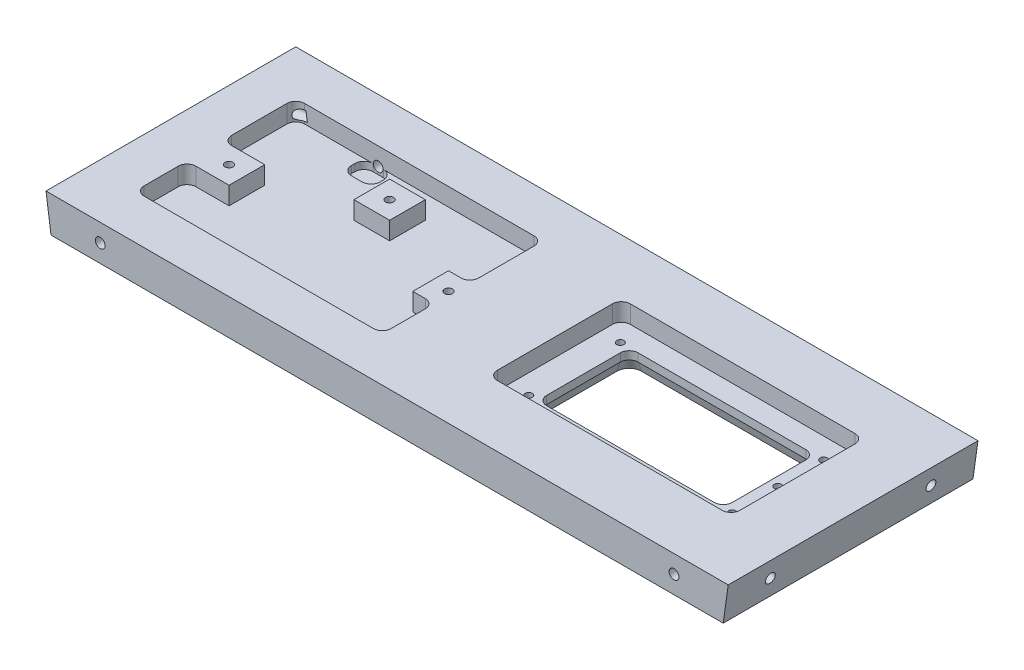
SolidWorks part; units mm, degrees
material "Oak"
ref_plane "Front Plane" through (0, 0, 0) normal (0, 0, 1) x (1, 0, 0)
ref_plane "Top Plane" through (0, 0, 0) normal (0, 1, 0) x (1, 0, 0)
ref_plane "Right Plane" through (0, 0, 0) normal (1, 0, 0) x (0, 0, -1)
sketch "Sketch1" plane through (0, 0, 0) normal (0, 0, 1) x (1, 0, 0)
  line L0 (0, 0) -> (0, -87.7011) construction
  line L1 (188.4017, -20) -> (-188.4017, -20)
  line L2 (-188.4017, -20) -> (-191.2125, 0)
  line L3 (-198.4942, -20.0415) -> (-240.8028, 281) construction
  line L4 (-191.2125, 0) -> (191.2125, 0)
  line L6 (188.4017, -20) -> (191.2125, 0)
  point P12 (0, 0)
  point P13 (0, -20)
  dimension "D1" = 20
  dimension "D2" = 10
extrude "Boss-Extrude1" add sketch "Sketch1" along normal blind 140
sketch "Sketch2" plane through (0, 0, 0) normal (0, 1, 0) x (1, 0, 0)
  line L0 (153.3, -105.5) -> (27.3, -105.5)
  line L1 (153.3, -100.5) -> (27.3, -100.5) construction
  line L2 (153.3, -100.5) -> (153.3, -36) construction
  line L3 (153.3, -36) -> (27.3, -36) construction
  line L4 (27.3, -100.5) -> (27.3, -36) construction
  line L5 (22.3, -100.5) -> (22.3, -36)
  line L6 (153.3, -31) -> (27.3, -31)
  line L7 (158.3, -100.5) -> (158.3, -36)
  line L8 (158.3, -31) -> (22.3, -31) construction
  line L9 (158.3, -105.5) -> (158.3, -31) construction
  line L10 (22.3, -105.5) -> (22.3, -31) construction
  line L11 (158.3, -105.5) -> (22.3, -105.5) construction
  arc A0 (153.3, -31) -> (158.3, -36) centre (153.3, -36) cw
  arc A1 (22.3, -36) -> (27.3, -31) centre (27.3, -36) cw
  arc A2 (27.3, -105.5) -> (22.3, -100.5) centre (27.3, -100.5) cw
  arc A3 (153.3, -105.5) -> (158.3, -100.5) centre (153.3, -100.5) ccw
  dimension "D2" = 5
  dimension "D1" = 5
extrude "Cut-Extrude1" cut sketch "Sketch2" against normal blind 10
sketch "Sketch3" plane through (0, -10, 0) normal (0, 1, 0) x (1, 0, 0)
  circle A0 centre (147.3, -42.6) radius 2
  circle A1 centre (147.3, -68.25) radius 2
  circle A2 centre (147.3, -93.9) radius 2
  circle A3 centre (33.3, -93.9) radius 2
  circle A4 centre (33.3, -42.6) radius 2
  dimension "D1" = 4
extrude "Cut-Extrude2" cut sketch "Sketch3" against normal blind 10
sketch "Sketch4" plane through (0, -10, 0) normal (0, 1, 0) x (1, 0, 0)
  line L1 (137.3, -93.9) -> (43.3, -93.9)
  line L2 (142.3, -88.9) -> (142.3, -47.6)
  line L3 (137.3, -42.6) -> (43.3, -42.6)
  line L4 (38.3, -88.9) -> (38.3, -47.6)
  arc A0 (142.3, -47.6) -> (137.3, -42.6) centre (137.3, -47.6) ccw
  arc A1 (43.3, -42.6) -> (38.3, -47.6) centre (43.3, -47.6) ccw
  arc A2 (43.3, -93.9) -> (38.3, -88.9) centre (43.3, -88.9) cw
  arc A3 (137.3, -93.9) -> (142.3, -88.9) centre (137.3, -88.9) ccw
  circle A4 centre (147.3, -68.25) radius 2 construction
  circle A5 centre (33.3, -42.6) radius 2 construction
  circle A6 centre (147.3, -42.6) radius 2 construction
  circle A7 centre (147.3, -93.9) radius 2 construction
  point P10 (38.3, -42.6)
  point P15 (142.3, -93.9)
  dimension "D1" = 5
  dimension "D2" = 5
  dimension "D3" = 5
  dimension "D4" = 0
  dimension "D5" = 0
extrude "Cut-Extrude3" cut sketch "Sketch4" against normal through all
chamfer "Chamfer2" distance 2 angle 70 8 edges at (90.3, -20, 93.9) (140.8355, -20, 92.4355) (39.7645, -20, 92.4355) (142.3, -20, 68.25) (38.3, -20, 68.25) (140.8355, -20, 44.0645) (39.7645, -20, 44.0645) (90.3, -20, 42.6)
sketch "Sketch5" plane through (0, -20, 0) normal (0, -1, 0) x (1, 0, 0)
  circle A0 centre (147.3, 42.6) radius 3.5
  circle A1 centre (147.3, 68.25) radius 3.5
  circle A2 centre (147.3, 93.9) radius 3.5
  circle A3 centre (33.3, 93.9) radius 3.5
  circle A4 centre (33.3, 42.6) radius 3.5
  dimension "D1" = 7
extrude "Cut-Extrude4" cut sketch "Sketch5" against normal blind 4
sketch "Sketch6" plane through (0, 0, 0) normal (0, 1, 0) x (1, 0, 0)
  circle A0 centre (-29.7, -75.9) radius 2.25
  circle A1 centre (-90.7, -47.9) radius 2.25
  circle A2 centre (-152.7, -75.9) radius 2.25
  dimension "D1" = 4.5
extrude "Cut-Extrude5" cut sketch "Sketch6" against normal through all
sketch "Sketch7" plane through (0, -20, 0) normal (0, -1, 0) x (1, 0, 0)
  circle A0 centre (-29.7, 75.9) radius 3.5
  circle A1 centre (-90.7, 47.9) radius 3.5
  circle A2 centre (-152.7, 75.9) radius 3.5
  dimension "D1" = 7
extrude "Cut-Extrude6" cut sketch "Sketch7" against normal blind 10
sketch "Sketch8" plane through (0, 0, 0) normal (0, 1, 0) x (1, 0, 0)
  line L0 (191.2125, 0) -> (-191.2125, 0) construction
  line L1 (191.2125, -12) -> (-191.2125, -12)
  line L2 (191.2125, -12) -> (191.2125, 0)
  line L3 (191.2125, 0) -> (-191.2125, 0)
  line L4 (-191.2125, -12) -> (-191.2125, 0)
  dimension "D1" = 12
extrude "Cut-Extrude7" [suppressed] cut sketch "Sketch8" against normal blind 1.5
sketch "Sketch9" plane through (-187.5089, -26.3527, 0) normal (-0.9903, -0.1392, 0) x (0, 0, 1)
  line L0 (70, -46.0258) -> (70, 104.6021) construction
  line L1 (140, -46.0258) -> (0, -46.0258) construction
  line L2 (140, 6.4151) -> (0, 6.4151) construction
  circle A0 centre (25, 16.5151) radius 2.75
  circle A1 centre (115, 16.5151) radius 2.75
  dimension "D1" = 90
  dimension "D3" = 5.5
  dimension "D2" = 10.1
extrude "Cut-Extrude8" cut sketch "Sketch9" against normal blind 30
mirror "Mirror1" about plane through (0, 0, 0) normal (1, 0, 0) of "Cut-Extrude8"
sketch "Sketch11" plane through (0, 0, 140) normal (0, 0, 1) x (1, 0, 0)
  line L1 (0, 98.6004) -> (0, -95.3458) construction
  line L2 (-188.4017, -20) -> (188.4017, -20) construction
  circle A0 centre (-160.8028, -10) radius 2.75
  circle A1 centre (160.8028, -10) radius 2.75
  dimension "D2" = 10
  dimension "D3" = 5.5
  dimension "D1" = 321.6056
extrude "Cut-Extrude9" cut sketch "Sketch11" against normal blind 30
sketch "Sketch12" plane through (0, 0, 0) normal (0, 0, -1) x (-1, 0, 0)
  line L0 (0, 0) -> (0, -85.5207) construction
  line L1 (188.4017, -20) -> (-188.4017, -20) construction
  circle A0 centre (120, -10) radius 2.75
  circle A1 centre (-120, -10) radius 2.75
  dimension "D1" = 5.5
  dimension "D3" = 10
  dimension "D2" = 120
  dimension "D4" = 240
extrude "Cut-Extrude10" cut sketch "Sketch12" against normal blind 30
sketch "Sketch13" plane through (0, 0, 0) normal (0, 1, 0) x (1, 0, 0)
  line L0 (-32.7, -115) -> (-161.2125, -115)
  line L1 (-166.2125, -110) -> (-166.2125, -90.9)
  line L2 (-161.2125, -85.9) -> (-142.7, -85.9)
  line L3 (-142.7, -85.9) -> (-142.7, -65.9)
  line L5 (-39.7, -65.9) -> (-39.7, -85.9)
  line L6 (-39.7, -85.9) -> (-32.7, -85.9)
  line L7 (-27.7, -90.9) -> (-27.7, -110)
  line L8 (-39.7, -65.9) -> (-32.7, -65.9)
  line L9 (-27.7, -60.9) -> (-27.7, -30)
  line L10 (-32.7, -25) -> (-161.2125, -25)
  line L11 (-166.2125, -30) -> (-166.2125, -60.9)
  line L12 (-161.2125, -65.9) -> (-142.7, -65.9)
  line L13 (-191.2125, -140) -> (-191.2125, 0) construction
  line L14 (-17.7, -123.8) -> (-17.7, -7.9) construction
  line L15 (191.2125, -140) -> (-191.2125, -140) construction
  line L16 (191.2125, 0) -> (-191.2125, 0) construction
  line L18 (-80.7, -57.9) -> (-100.7, -57.9)
  line L19 (-80.7, -57.9) -> (-80.7, -37.9)
  line L20 (-80.7, -37.9) -> (-100.7, -37.9)
  line L21 (-100.7, -57.9) -> (-100.7, -37.9)
  line L22 (-80.7, -57.9) -> (-100.7, -37.9) construction
  line L23 (-80.7, -37.9) -> (-100.7, -57.9) construction
  circle A0 centre (-152.7, -75.9) radius 2.25 construction
  circle A1 centre (-29.7, -75.9) radius 2 construction
  arc A2 (-32.7, -65.9) -> (-27.7, -60.9) centre (-32.7, -60.9) ccw
  arc A3 (-27.7, -30) -> (-32.7, -25) centre (-32.7, -30) ccw
  arc A4 (-161.2125, -25) -> (-166.2125, -30) centre (-161.2125, -30) ccw
  arc A5 (-166.2125, -60.9) -> (-161.2125, -65.9) centre (-161.2125, -60.9) ccw
  arc A6 (-166.2125, -90.9) -> (-161.2125, -85.9) centre (-161.2125, -90.9) cw
  arc A7 (-161.2125, -115) -> (-166.2125, -110) centre (-161.2125, -110) cw
  arc A8 (-27.7, -110) -> (-32.7, -115) centre (-32.7, -110) cw
  arc A9 (-32.7, -85.9) -> (-27.7, -90.9) centre (-32.7, -90.9) cw
  point P10 (-90.7, -47.9)
  dimension "D11" = 5
  dimension "D1" = 25
  dimension "D2" = 10
  dimension "D3" = 25
  dimension "D4" = 25
  dimension "D5" = 20
  dimension "D6" = 20
  dimension "D7" = 10
  dimension "D8" = 20
  dimension "D9" = 10
  dimension "D10" = 10
extrude "Cut-Extrude11" cut sketch "Sketch13" against normal blind 10
sketch "Sketch14" plane through (0, -10, 0) normal (0, 1, 0) x (1, 0, 0)
  line L0 (-32.7, -25) -> (-161.2125, -25) construction
  line L1 (-117, -37) -> (-123, -37)
  line L2 (-112, -32) -> (-112, -30)
  line L3 (-117, -25) -> (-123, -25)
  line L4 (-128, -32) -> (-128, -30)
  line L5 (-112, -37) -> (-128, -25) construction
  line L6 (-112, -25) -> (-128, -37) construction
  line L16 (-120, -30) -> (-120, -31) construction
  line L17 (-122.75, -30) -> (-117.25, -30) construction
  line L23 (-158.0528, -110) -> (-163.5528, -110) construction
  line L25 (-166.2125, -90.9) -> (-166.2125, -110) construction
  line L26 (-157.9125, -105) -> (-161.2125, -105)
  line L27 (-157.9125, -115) -> (-161.2125, -115)
  arc A2 (-117, -37) -> (-112, -32) centre (-117, -32) ccw
  arc A3 (-123, -37) -> (-128, -32) centre (-123, -32) cw
  arc A4 (-112, -30) -> (-117, -25) centre (-117, -30) ccw
  arc A5 (-123, -25) -> (-128, -30) centre (-123, -30) ccw
  arc A10 (-157.9125, -115) -> (-157.9125, -105) centre (-157.9125, -110) ccw
  arc A11 (-161.2125, -105) -> (-161.2125, -115) centre (-161.2125, -110) ccw
  point P0 (-120, -31)
  dimension "D3" = 5
  dimension "D4" = 5
  dimension "D1" = 5
  dimension "D6" = 3.3
  dimension "D7" = 5
  dimension "D2" = 16
  dimension "D5" = 2
extrude "Cut-Extrude12" cut sketch "Sketch14" against normal blind 4
sketch "Sketch15" plane through (0, -20, 0) normal (0, -1, 0) x (1, 0, 0)
  line L0 (147.3, 71.75) -> (142.3, 71.75)
  line L1 (142.3, 47.6) -> (142.3, 88.9) construction
  line L2 (142.3, 71.75) -> (142.3, 64.75)
  line L3 (142.3, 64.75) -> (147.3, 64.75)
  circle A0 centre (147.3, 68.25) radius 3.5 construction
  arc A1 (147.3, 64.75) -> (147.3, 71.75) centre (147.3, 68.25) ccw
extrude "Cut-Extrude13" cut sketch "Sketch15" against normal up to surface (4 mm away) up to face at (147.3, -16, 64.75)
